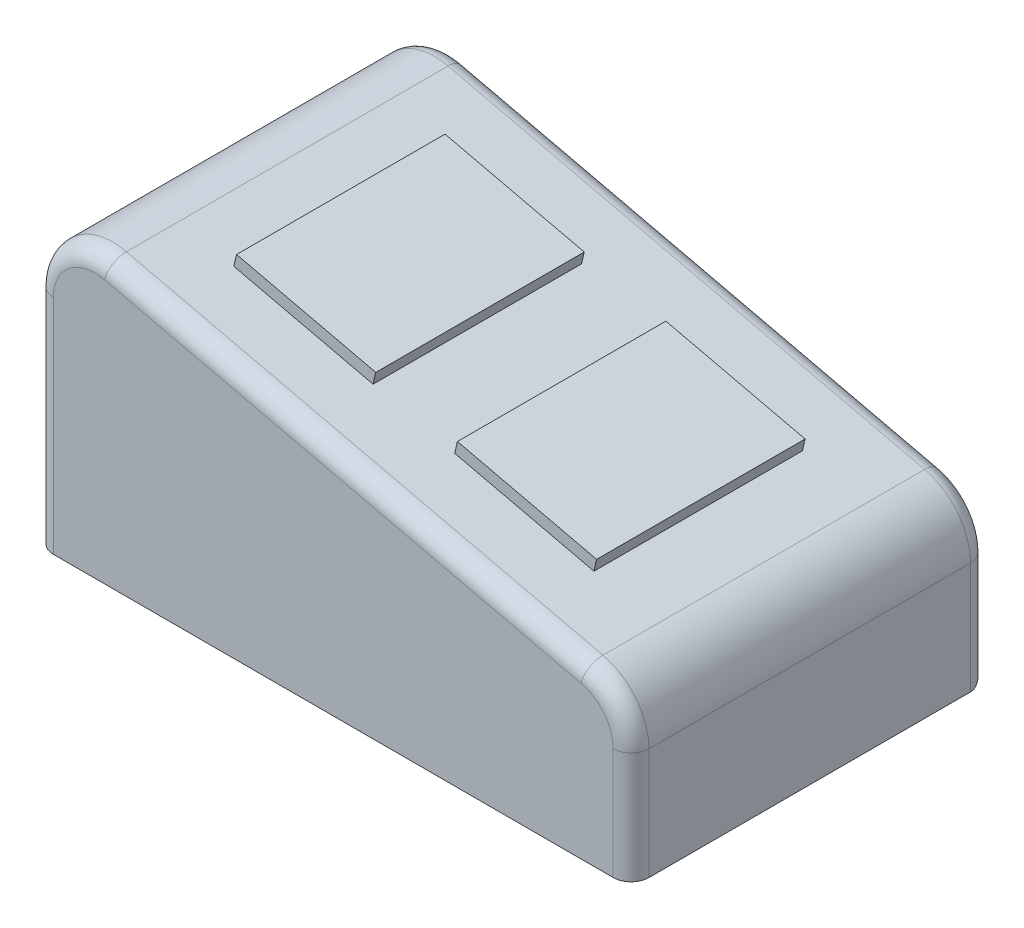
SolidWorks part; units mm, degrees
ref_plane "Front Plane" through (0, 0, 0) normal (0, 0, 1) x (1, 0, 0)
ref_plane "Top Plane" through (0, 0, 0) normal (0, 1, 0) x (1, 0, 0)
ref_plane "Right Plane" through (0, 0, 0) normal (1, 0, 0) x (0, 0, -1)
sketch "Sketch1" plane through (0, 0, 0) normal (0, 0, 1) x (1, 0, 0)
  line L0 (-54.7441, 4.2056) -> (25.2559, -14.4549)
  line L2 (-67.0157, -5.5329) -> (-67.0157, -42.9319)
  line L3 (-67.0157, -42.9319) -> (32.9843, -42.9319)
  line L4 (32.9843, -24.1935) -> (32.9843, -42.9319)
  arc A0 (32.9843, -24.1935) -> (25.2559, -14.4549) centre (22.9843, -24.1935) ccw
  arc A1 (-54.7441, 4.2056) -> (-67.0157, -5.5329) centre (-57.0157, -5.5329) ccw
  point P8 (-67.0157, 7.0681)
  dimension "D3" = 10
  dimension "D1" = 100
  dimension "D2" = 50
extrude "Boss-Extrude1" add sketch "Sketch1" against normal blind 60
sketch "Sketch2" plane through (-1.8945, -8.1219, 0) normal (0.2272, 0.9739, 0) x (0.9739, -0.2272, 0)
  line L0 (27.8792, 0) -> (-54.2683, 0) construction
  line L1 (-44.9921, 47) -> (-20.9921, 47)
  line L2 (-44.9921, 47) -> (-44.9921, 12)
  line L3 (-44.9921, 12) -> (-20.9921, 12)
  line L4 (-20.9921, 47) -> (-20.9921, 12)
  line L5 (-6.9158, 47) -> (17.0842, 47)
  line L6 (-6.9158, 47) -> (-6.9158, 12)
  line L7 (-6.9158, 12) -> (17.0842, 12)
  line L8 (17.0842, 47) -> (17.0842, 12)
  dimension "D1" = 35
  dimension "D2" = 35
  dimension "D3" = 12
  dimension "D4" = 24
  dimension "D5" = 12
  dimension "D6" = 24
extrude "Boss-Extrude2" add sketch "Sketch2" along normal blind 2
fillet "Fillet1" radius 3 11 edges at (-67.0157, -24.2324, 0) (-63.232, 2.3002, 0) (-14.7441, -5.1246, 0) (30.8174, -17.9772, 0) (32.9843, -33.5627, 0) (30.8174, -17.9772, -60) (-14.7441, -5.1246, -60) (-63.232, 2.3002, -60) (-67.0157, -24.2324, -60) (-17.0157, -42.9319, -60) (32.9843, -33.5627, -60)
